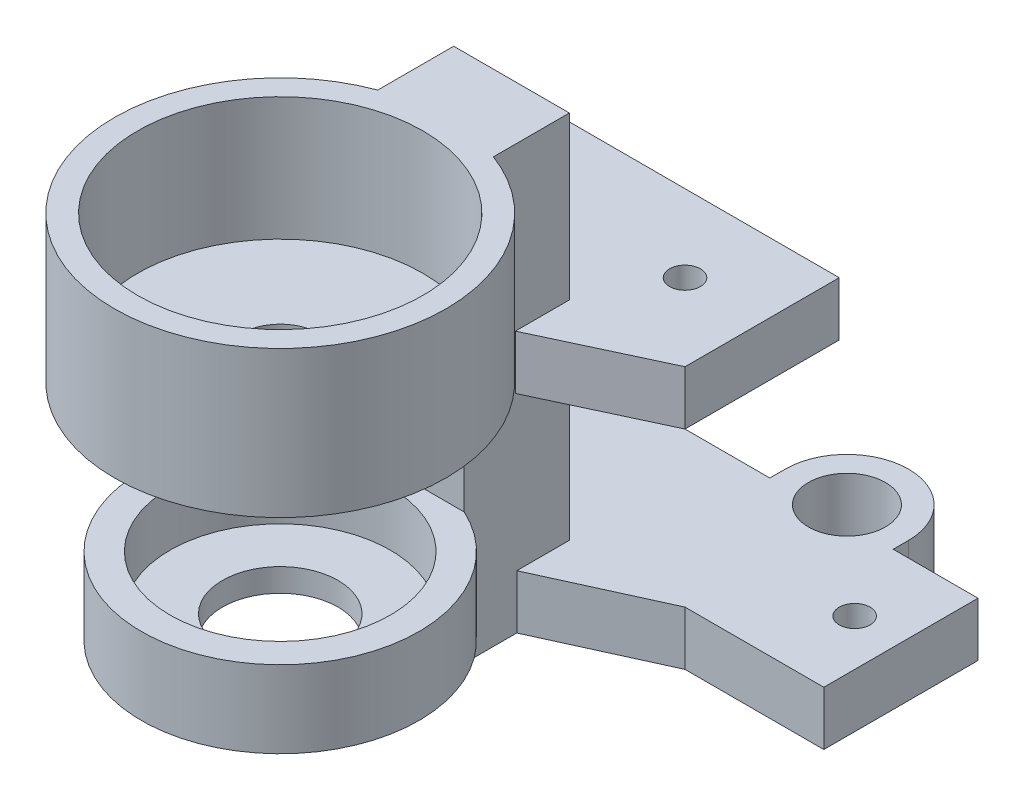
SolidWorks part; units mm, degrees
ref_plane "Plan de face" through (0, 0, 0) normal (0, 0, 1) x (1, 0, 0)
ref_plane "Plan de dessus" through (0, 0, 0) normal (0, 1, 0) x (1, 0, 0)
ref_plane "Plan de droite" through (0, 0, 0) normal (1, 0, 0) x (0, 0, -1)
sketch "Esquisse1" plane through (0, 0, 0) normal (0, 1, 0) x (1, 0, 0)
  line L1 (0, 0) -> (36, 0)
  line L2 (0, 0) -> (0, 20)
  line L3 (0, 20) -> (36, 20)
  line L4 (36, 0) -> (36, 20)
  dimension "D1" = 36
  dimension "D2" = 20
extrude "Boss.-Extru.1" add sketch "Esquisse1" along normal blind 5
sketch "Esquisse2" plane through (0, 5, 0) normal (0, 1, 0) x (1, 0, 0)
  line L0 (0, 0) -> (36, 0) construction
  line L1 (10.5, 0) -> (25.5, 0)
  line L2 (10.5, 0) -> (10.5, 10.5912)
  line L3 (10.5, 10.5912) -> (25.5, 10.5912)
  line L4 (25.5, 0) -> (25.5, 10.5912)
  line L5 (0, 20) -> (0, 0) construction
  line L7 (10.5, 10.5912) -> (25.5, 10.5912)
  line L8 (10.5, 10.5912) -> (10.5, 14.5912)
  line L9 (10.5, 14.5912) -> (25.5, 14.5912)
  line L10 (25.5, 10.5912) -> (25.5, 14.5912)
  dimension "D1" = 15
  dimension "D2" = 10.5
  dimension "D3" = 4
extrude "Boss.-Extru.2" add sketch "Esquisse2" along normal blind 32 contours L2 L1 L4 L3 | L8 L7 L10 L9
sketch "Esquisse3" plane through (0, 37, 0) normal (0, 1, 0) x (1, 0, 0)
  line L1 (10.5, 0) -> (25.5, 0)
  line L2 (10.5, 0) -> (10.5, -37.5)
  line L3 (10.5, -37.5) -> (25.5, -37.5)
  line L4 (25.5, 0) -> (25.5, -37.5)
  circle A0 centre (18, -30) radius 5
  circle A1 centre (18, -30) radius 7.5
  circle A2 centre (18, -30) radius 7.5
  dimension "D2" = 10
  dimension "D3" = 30
  dimension "D1" = 15
  dimension "D4" = 37.5
  dimension "D5" = 7.5
extrude "Boss.-Extru.3" add sketch "Esquisse3" along normal blind 6
sketch "Esquisse4" plane through (0, 43, 0) normal (0, 1, 0) x (1, 0, 0)
  circle A0 centre (18, -30) radius 18.5
  circle A1 centre (18, -30) radius 21.5
  circle A2 centre (18, -30) radius 5
extrude "Boss.-Extru.4" add sketch "Esquisse4" along normal blind 16
sketch "Esquisse5" plane through (0, 43, 0) normal (0, 1, 0) x (1, 0, 0)
  circle A0 centre (18, -30) radius 7.5
  circle A1 centre (18, -30) radius 21.5
extrude "Boss.-Extru.5" add sketch "Esquisse5" against normal blind 3
sketch "Esquisse6" plane through (0, 43, 0) normal (0, 1, 0) x (1, 0, 0)
  line L1 (10.5, 14.5912) -> (25.5, 14.5912)
  line L2 (10.5, 14.5912) -> (10.5, 11.178)
  line L3 (10.5, 11.178) -> (25.5, 11.178)
  line L4 (25.5, 14.5912) -> (25.5, 11.178)
extrude "Boss.-Extru.6" add sketch "Esquisse6" along normal blind 16
sketch "Esquisse8" plane through (0, 0, 0) normal (0, -1, 0) x (1, 0, 0)
  line L0 (0, -20) -> (0, 0) construction
  line L1 (36, 0) -> (36, -20) construction
  line L2 (36, -20) -> (0, -20) construction
  circle A0 centre (6, -10) radius 2
  circle A1 centre (30, -10) radius 2
  dimension "D1" = 4
  dimension "D2" = 4
  dimension "D3" = 6
  dimension "D4" = 6
  dimension "D5" = 10
  dimension "D6" = 10
extrude "Enlèv. mat.-Extru.1" cut sketch "Esquisse8" against normal blind 16
sketch "Esquisse9" plane through (0, 0, 0) normal (0, 0, 1) x (1, 0, 0)
  line L0 (25.5, 37) -> (25.5, 5) construction
  line L1 (10.5, 37) -> (25.5, 37)
  line L2 (10.5, 37) -> (10.5, 21)
  line L3 (10.5, 21) -> (25.5, 21)
  line L4 (25.5, 37) -> (25.5, 21)
  line L6 (10.5, 21) -> (25.5, 21)
  line L7 (10.5, 21) -> (10.5, 11)
  line L8 (10.5, 11) -> (25.5, 11)
  line L9 (25.5, 21) -> (25.5, 11)
  line M6 (25.5, 5) -> (25.5, 37)
  line M8 (10.5, 37) -> (10.5, 5)
  dimension "D1" = 16
  dimension "D2" = 10
extrude "Boss.-Extru.7" add sketch "Esquisse9" along normal blind 30 contours L8 L3 M8 M6
sketch "Esquisse10" plane through (0, 11, 0) normal (0, -1, 0) x (1, 0, 0)
  line L0 (10.5, 30) -> (25.5, 30) construction
  circle A0 centre (18, 30) radius 15
  circle A1 centre (18, 30) radius 21.5
extrude "Boss.-Extru.8" add sketch "Esquisse10" against normal up to vertex contours A0 | A1
sketch "Esquisse11" plane through (0, 11, 0) normal (0, -1, 0) x (1, 0, 0)
  line L0 (10.5, 30) -> (25.5, 30) construction
  circle A0 centre (18, 30) radius 15
  circle A1 centre (18, 30) radius 7.5
extrude "Boss.-Extru.9" add sketch "Esquisse11" against normal blind 3
sketch "Esquisse12" plane through (0, 21, 0) normal (0, 1, 0) x (1, 0, 0)
  line L0 (10.5, -30) -> (25.5, -30) construction
  circle A0 centre (18, -30) radius 15
extrude "Enlèv. mat.-Extru.2" cut sketch "Esquisse12" against normal blind 7
sketch "Esquisse13" plane through (0, 11, 0) normal (0, -1, 0) x (1, 0, 0)
  line L0 (10.5, 30) -> (25.5, 30) construction
  circle A0 centre (18, 30) radius 7.5
extrude "Enlèv. mat.-Extru.3" cut sketch "Esquisse13" against normal blind 7
sketch "Esquisse14" plane through (0, 14, 0) normal (0, 1, 0) x (1, 0, 0)
  circle A0 centre (18, -30) radius 15
  circle A1 centre (18, -30) radius 14.295
  dimension "D1" = 28.59
extrude "Boss.-Extru.10" add sketch "Esquisse14" along normal blind 7
sketch "Esquisse15" plane through (0, 11, 0) normal (0, -1, 0) x (1, 0, 0)
  line L1 (10.5, 0) -> (25.5, 0)
  line L2 (10.5, 0) -> (10.5, 15)
  line L3 (10.5, 15) -> (25.5, 15)
  line L4 (25.5, 0) -> (25.5, 15)
  circle A0 centre (18, 30) radius 21.5
  circle A1 centre (18, 30) radius 18
  arc M2 (25.5, 9.8506) -> (10.5, 9.8506) centre (18, 30) ccw
  dimension "D1" = 15
extrude "Enlèv. mat.-Extru.4" cut sketch "Esquisse15" against normal blind 10 contours A1 L4 L2 M2
sketch "Esquisse16" plane through (0, 0, -11.178) normal (0, 0, 1) x (1, 0, 0)
  line L1 (25.5, 43) -> (10.5, 43)
  line L2 (25.5, 43) -> (25.5, 59)
  line L3 (25.5, 59) -> (10.5, 59)
  line L4 (10.5, 43) -> (10.5, 59)
extrude "Boss.-Extru.11" add sketch "Esquisse16" along normal blind 22
sketch "Esquisse18" plane through (0, 21, 0) normal (0, 1, 0) x (1, 0, 0)
  line L1 (25.5, 0) -> (10.5, 0)
  line L2 (25.5, 0) -> (25.5, -13.6369)
  line L3 (25.5, -13.6369) -> (10.5, -13.6369)
  line L4 (10.5, 0) -> (10.5, -13.6369)
extrude "Boss.-Extru.12" add sketch "Esquisse18" along normal blind 22
sketch "Esquisse19" plane through (0, 0, 0) normal (0, -1, 0) x (1, 0, 0)
  line L1 (0, 0) -> (36, 0)
  line L2 (0, 0) -> (0, -20)
  line L3 (0, -20) -> (36, -20)
  line L4 (36, 0) -> (36, -20)
extrude "Enlèv. mat.-Extru.5" cut sketch "Esquisse19" against normal through all
sketch "Esquisse20" plane through (0, 0, 0) normal (0, 0, -1) x (-1, 0, 0)
  line L0 (-10.5, 11) -> (-10.5, 59) construction
  line L1 (-25.5, 11) -> (-10.5, 11)
  line L2 (-25.5, 11) -> (-25.5, 31)
  line L3 (-25.5, 31) -> (-10.5, 31)
  line L4 (-10.5, 11) -> (-10.5, 31)
  line L6 (-25.5, 31) -> (-10.5, 31)
  line L7 (-25.5, 31) -> (-25.5, 38)
  line L8 (-25.5, 38) -> (-10.5, 38)
  line L9 (-10.5, 31) -> (-10.5, 38)
  line M3 (-10.5, 11) -> (-10.5, 59)
  line M5 (-25.5, 59) -> (-25.5, 11)
  dimension "D1" = 20
  dimension "D2" = 7
extrude "Boss.-Extru.13" add sketch "Esquisse20" along normal blind 20 contours L8 L3 M5 M3
sketch "Esquisse22" plane through (10.5, 0, 0) normal (-1, 0, 0) x (0, 0, 1)
  line L1 (-20, 38) -> (7, 38)
  line L2 (-20, 38) -> (-20, 31)
  line L3 (-20, 31) -> (7, 31)
  line L4 (7, 38) -> (7, 31)
  dimension "D1" = 27
extrude "Boss.-Extru.14" add sketch "Esquisse22" along normal blind 15 and the other way blind 30
sketch "Esquisse23" plane through (0, 38, 0) normal (0, 1, 0) x (1, 0, 0)
  line L0 (10.5, -7) -> (-4.5, 0)
  line L1 (-4.5, -7) -> (-4.5, 20) construction
  line L2 (-4.5, 0) -> (40.5, 0)
  line L3 (40.5, -7) -> (40.5, 20) construction
  line L4 (40.5, 0) -> (25.5, -7)
  line L5 (40.5, 20) -> (-4.5, 20) construction
  circle A0 centre (30.5, 10) radius 2
  circle A1 centre (5.5, 10) radius 2
  line M4 (25.5, -7) -> (40.5, -7)
  line M5 (40.5, -7) -> (40.5, 20)
  line M7 (-4.5, 20) -> (-4.5, -7)
  line M8 (-4.5, -7) -> (10.5, -7)
  dimension "D5" = 4
  dimension "D6" = 4
  dimension "D1" = 10
  dimension "D2" = 10
  dimension "D3" = 10
  dimension "D4" = 10
extrude "Enlèv. mat.-Extru.6" cut sketch "Esquisse23" against normal through all contours A0 | A1 | L0 M8 M7 | L4 M5 M4
sketch "Esquisse24" plane through (0, 11, 0) normal (0, -1, 0) x (1, 0, 0)
  line L0 (10.5, 13.6369) -> (10.5, 0) construction
  line L1 (-4.5, 0) -> (40.5, 0)
  line L2 (-4.5, 0) -> (-4.5, -20)
  line L3 (-4.5, -20) -> (40.5, -20)
  line L4 (40.5, 0) -> (40.5, -20)
  line L5 (10.5, 6.8185) -> (25.5, 6.8185)
  line L6 (10.5, 6.8185) -> (10.5, 0)
  line L7 (10.5, 0) -> (25.5, 0)
  line L8 (25.5, 6.8185) -> (25.5, 0)
  line L9 (10.5, 6.8185) -> (-4.5, 0)
  line L10 (25.5, 6.8185) -> (40.5, 0)
  line L12 (10.5, 6.8185) -> (25.5, 6.8185)
  line L13 (10.5, 6.8185) -> (10.5, 13.6369)
  line L14 (10.5, 13.6369) -> (25.5, 13.6369)
  line L15 (25.5, 6.8185) -> (25.5, 13.6369)
  circle A1 centre (5.5, -10) radius 2
  line M2 (10.5, 13.6369) -> (10.5, 0)
  line M3 (10.5, 0) -> (25.5, 0)
  line M4 (25.5, 0) -> (25.5, 13.6369)
extrude "Boss.-Extru.15" add sketch "Esquisse24" along normal blind 7 contours L4 L1 L2 L3 M3 | L5 M2 M3 M4 | L10 L1 M4 | L9 L1 M2 | L14 L5 M2 M4
sketch "Esquisse25" plane through (0, 4, 0) normal (0, -1, 0) x (-1, 0, 0)
  line L0 (-40.5, 0) -> (-40.5, 20) construction
  line L1 (4.5, 20) -> (-40.5, 20) construction
  line L2 (-47.5, 22) -> (-47.5, 20)
  line L3 (-40.5, 0) -> (-58.5, 0)
  line L4 (-40.5, 0) -> (-40.5, 20)
  line L5 (-40.5, 20) -> (-58.5, 20)
  line L6 (-58.5, 0) -> (-58.5, 20)
  line L7 (-31.5, 22) -> (-31.5, 20)
  circle A0 centre (-39.5, 22) radius 5
  circle A1 centre (-39.5, 22) radius 8
  circle A2 centre (-52.5, 10) radius 2
  circle A3 centre (-5.5, 10) radius 2 construction
  line M8 (4.5, 20) -> (-40.5, 20)
  line M9 (-40.5, 20) -> (-40.5, 0)
  dimension "D1" = 1
  dimension "D3" = 20
  dimension "D5" = 0
  dimension "D6" = 6
  dimension "D2" = 2
  dimension "D4" = 18
extrude "Boss.-Extru.16" add sketch "Esquisse25" against normal blind 7 contours A1 L5 A0 M8 | L5 A1 L4 M9 | A1 L5 L6 L3 A2 M9 | A0 M8 M9 | L4 A1 A0 M8 | A1 L2 L5 | A1 L7 M8
sketch "Esquisse27" plane through (0, 4, 0) normal (0, -1, 0) x (1, 0, 0)
  circle A0 centre (39.5, -22) radius 5
extrude "Enlèv. mat.-Extru.7" cut sketch "Esquisse27" against normal blind 7
sketch "Esquisse28" plane through (0, 4, 0) normal (0, -1, 0) x (1, 0, 0)
  circle A0 centre (39.5, -22) radius 5
  circle A1 centre (39.5, -22) radius 8
extrude "Boss.-Extru.18" add sketch "Esquisse28" along normal blind 5
